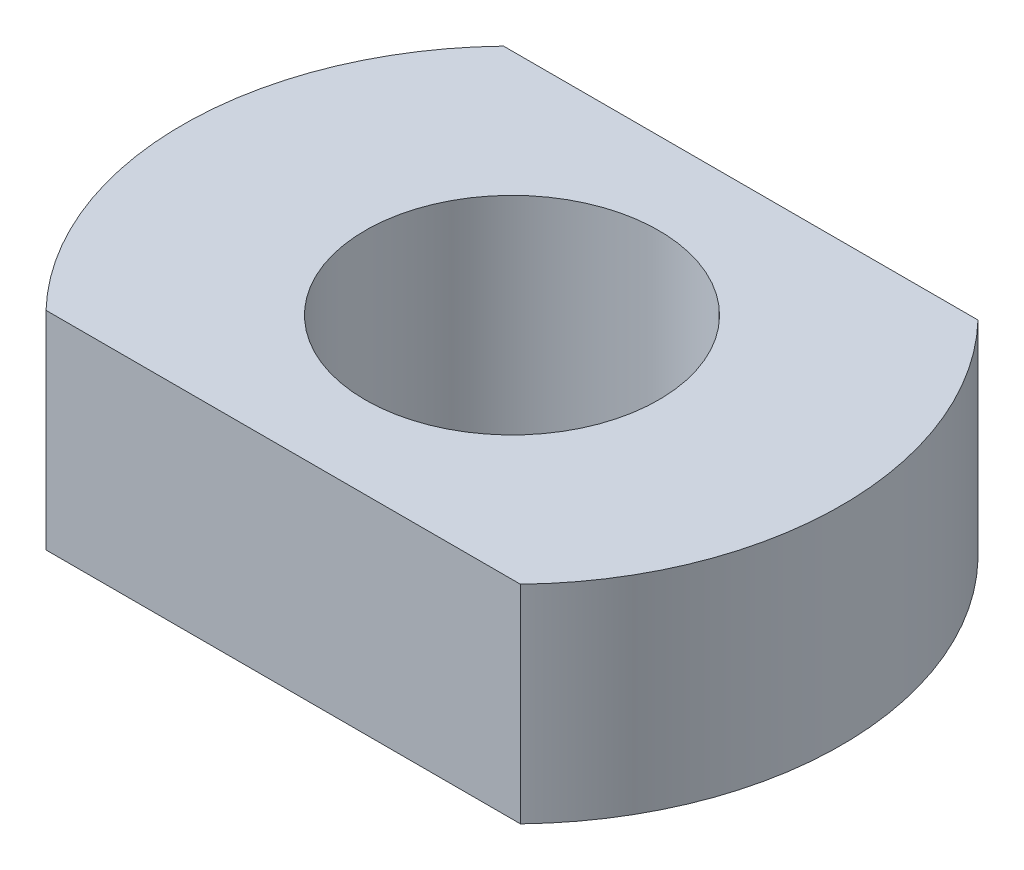
SolidWorks part; units mm, degrees
ref_plane "Front Plane" through (0, 0, 0) normal (0, 0, 1) x (1, 0, 0)
ref_plane "Top Plane" through (0, 0, 0) normal (0, 1, 0) x (1, 0, 0)
ref_plane "Right Plane" through (0, 0, 0) normal (1, 0, 0) x (0, 0, -1)
sketch "Sketch1" plane through (0, 0, 0) normal (0, 1, 0) x (1, 0, 0)
  line L0 (-8, 7.7164) -> (8, 7.7164)
  line L1 (0, -11.115) -> (0, 62.3957)
  line L2 (-8, -7.7164) -> (8, -7.7164)
  circle A0 centre (0, 0) radius 11.115
  circle A2 centre (0, 0) radius 4.95
  dimension "D2" = 22.23
  dimension "D3" = 16
  dimension "D4" = 9.9
  dimension "D1" = 16
extrude "Boss-Extrude2" add sketch "Sketch1" along normal blind 7
